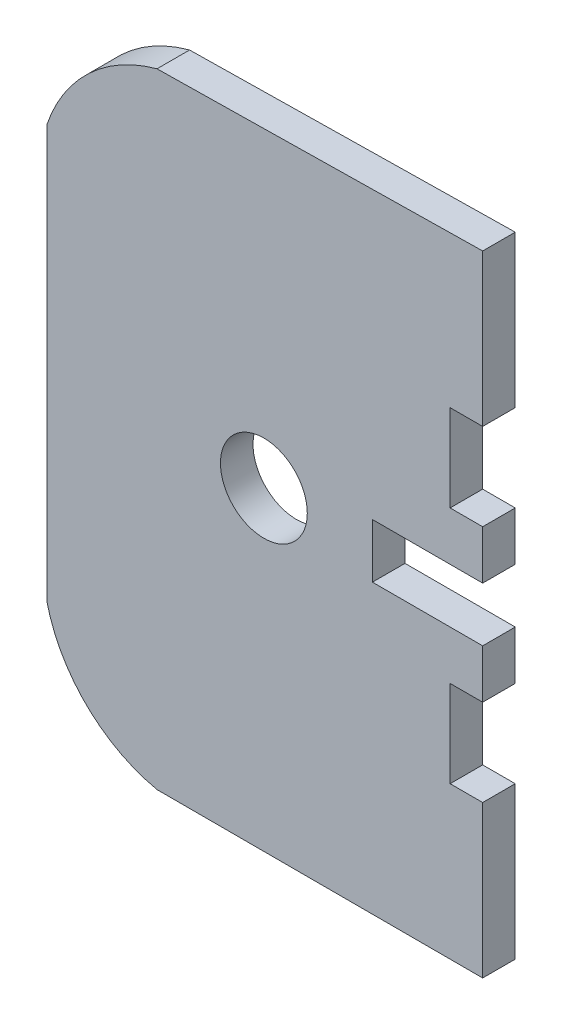
SolidWorks part; units mm, degrees
material "Oak"
ref_plane "Front Plane" through (0, 0, 0) normal (0, 0, 1) x (1, 0, 0)
ref_plane "Top Plane" through (0, 0, 0) normal (0, 1, 0) x (1, 0, 0)
ref_plane "Right Plane" through (0, 0, 0) normal (1, 0, 0) x (0, 0, -1)
sketch "Sketch1" plane through (0, 0, 0) normal (0, 0, 1) x (1, 0, 0)
  line L0 (104.1192, 179.4071) -> (134.1192, 179.8744)
  line L1 (93.9632, 169.8532) -> (93.9632, 131.8957)
  line L2 (104.1192, 121.9034) -> (134.1192, 121.8744)
  line L3 (134.1192, 165.8744) -> (131.1192, 165.8744)
  line L4 (134.1192, 121.8744) -> (134.1192, 179.8744) construction
  line L5 (93.9632, 150.8744) -> (123.9632, 150.8744) construction
  line L6 (131.1192, 157.8744) -> (134.1192, 157.8744)
  line L7 (134.1192, 165.8744) -> (134.1192, 179.8744)
  line L8 (134.1192, 157.8744) -> (134.1192, 153.3743)
  line L9 (134.1192, 143.8744) -> (131.1192, 143.8744)
  line L10 (131.1192, 157.8744) -> (131.1192, 165.8744)
  line L11 (131.1192, 135.8744) -> (134.1192, 135.8744)
  line L12 (134.1192, 148.3743) -> (134.1192, 143.8744)
  line L13 (134.1192, 148.3743) -> (123.9632, 148.3743)
  line L14 (131.1192, 135.8744) -> (131.1192, 143.8744)
  line L15 (134.1192, 135.8744) -> (134.1192, 121.8744)
  line L16 (134.1192, 153.3743) -> (123.9632, 153.3743)
  line L17 (123.9632, 148.3743) -> (123.9632, 153.3743)
  line L22 (134.1192, 179.8744) -> (134.1192, 165.8744)
  circle A0 centre (113.9632, 150.8744) radius 4
  arc A1 (93.9632, 131.8957) -> (104.1192, 121.9034) centre (106.915, 134.9023) ccw
  arc A2 (104.1192, 179.4071) -> (93.9632, 169.8532) centre (107.9738, 165.1345) ccw
  point P1 (134.1519, 165.7918)
  point P4 (134.2213, 136.0035)
  dimension "D1" = 14
  dimension "D2" = 14
  dimension "D4" = 3
  dimension "D15" = 5
  dimension "D3" = 14
  dimension "D5" = 8
  dimension "D6" = 8
  dimension "D10" = 30
  dimension "D11" = 30
extrude "Boss-Extrude1" add sketch "Sketch1" along normal blind 3
